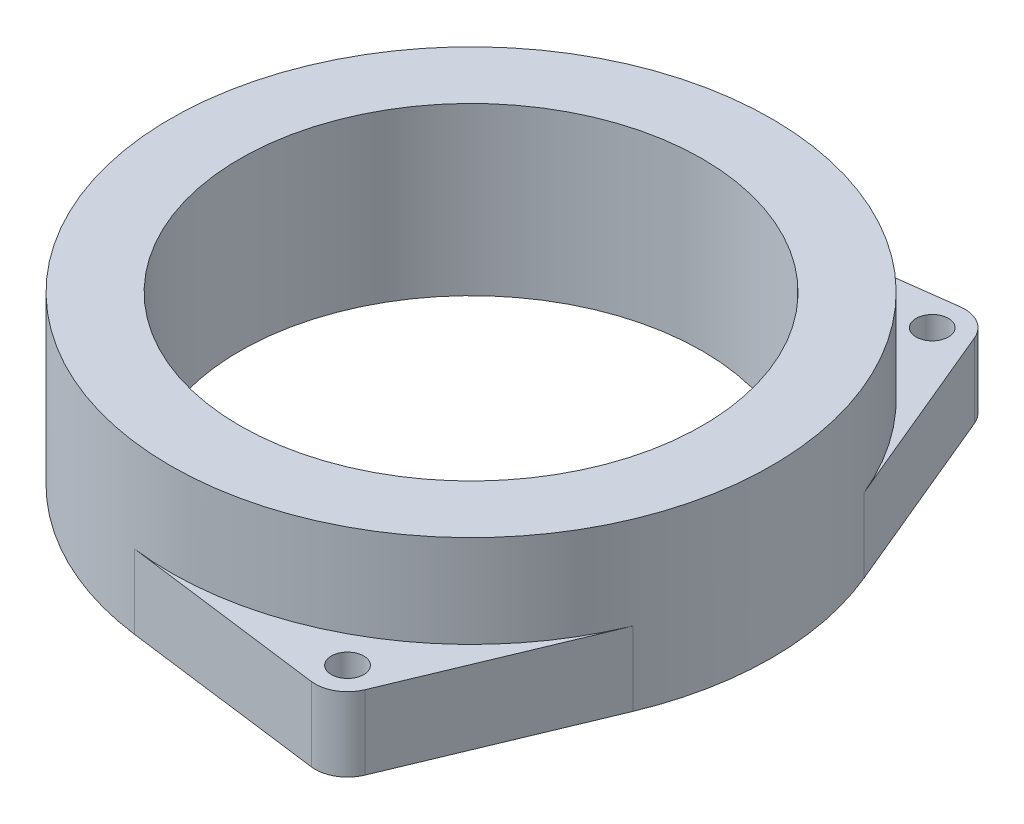
SolidWorks part; units mm, degrees
ref_plane "Alzado" through (0, 0, 0) normal (0, 0, 1) x (1, 0, 0)
ref_plane "Planta" through (0, 0, 0) normal (0, 1, 0) x (1, 0, 0)
ref_plane "Vista lateral" through (0, 0, 0) normal (1, 0, 0) x (0, 0, -1)
sketch "Croquis1" plane through (0, 0, 0) normal (0, 1, 0) x (1, 0, 0)
  line L0 (0, 0) -> (-32.5, 0) construction
  line L1 (-39.2808, 2.1253) -> (-25.8219, 19.7352)
  line L2 (-39.2808, -2.1253) -> (-25.8219, -19.7352)
  line L3 (21.481, 32.9555) -> (30.0022, 12.4948)
  line L4 (17.7998, 35.0809) -> (-4.1802, 32.23)
  line L5 (17.7998, -35.0809) -> (-4.1802, -32.23)
  line L6 (21.481, -32.9555) -> (30.0022, -12.4948)
  line L7 (0, 0) -> (-25.8219, 19.7352) construction
  arc A0 (-25.8219, -19.7352) -> (-4.1802, -32.23) centre (0, 0) ccw
  arc A1 (-39.2808, 2.1253) -> (-39.2808, -2.1253) centre (-36.5, 0) ccw
  arc A2 (21.481, 32.9555) -> (17.7998, 35.0809) centre (18.25, 31.6099) ccw
  arc A3 (17.7998, -35.0809) -> (21.481, -32.9555) centre (18.25, -31.6099) ccw
  arc A4 (-4.1802, 32.23) -> (-25.8219, 19.7352) centre (0, 0) ccw
  arc A5 (30.0022, -12.4948) -> (30.0022, 12.4948) centre (0, 0) ccw
  circle A6 centre (0, 0) radius 25
  circle A7 centre (18.25, 31.6099) radius 1.75
  circle A8 centre (-36.5, 0) radius 1.75
  circle A9 centre (18.25, -31.6099) radius 1.75
  dimension "D1" = 7
  dimension "D5" = 50
  dimension "D6" = 3.5
  dimension "D2" = 32.5
  dimension "D3" = 4
  dimension "D4" = 32.5
extrude "Saliente-Extruir1" add sketch "Croquis1" along normal blind 8
sketch "Croquis2" plane through (0, 8, 0) normal (0, 1, 0) x (1, 0, 0)
  circle A0 centre (0, 0) radius 25 construction
  circle A1 centre (0, 0) radius 25
  circle A2 centre (0, 0) radius 32.5
extrude "Saliente-Extruir2" add sketch "Croquis2" along normal blind 10
